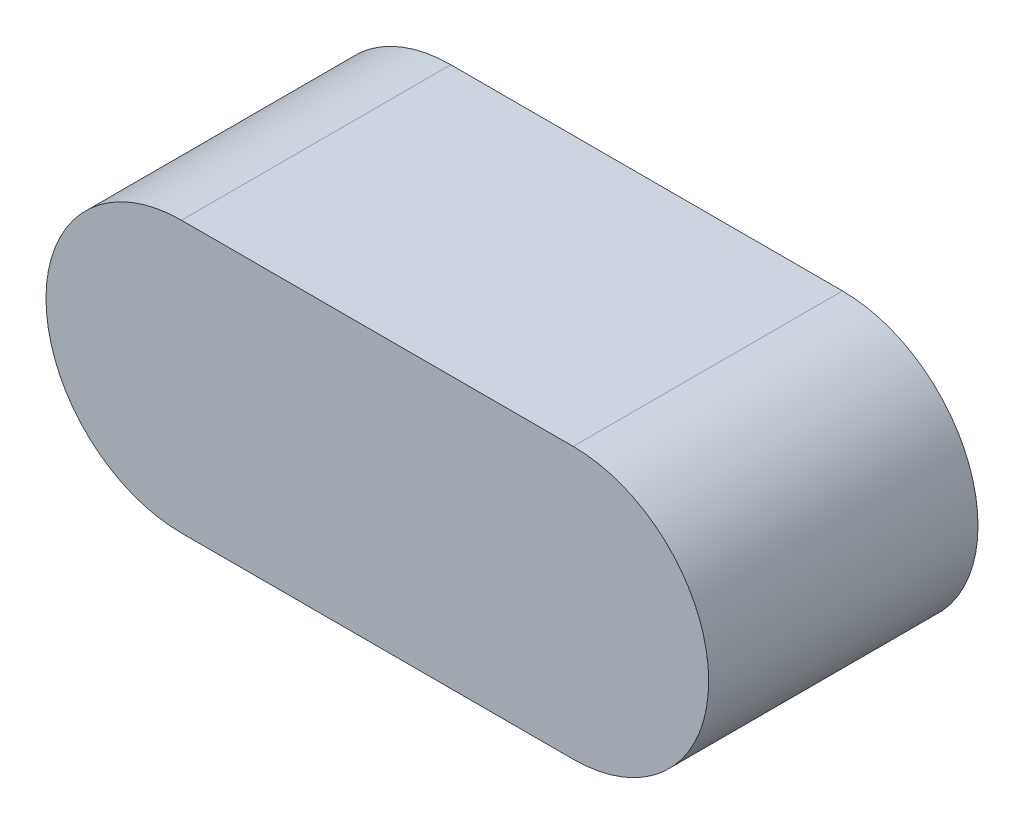
SolidWorks part; units mm, degrees
ref_plane "Plan de face" through (0, 0, 0) normal (0, 0, 1) x (1, 0, 0)
ref_plane "Plan de dessus" through (0, 0, 0) normal (0, 1, 0) x (1, 0, 0)
ref_plane "Plan de droite" through (0, 0, 0) normal (1, 0, 0) x (0, 0, -1)
sketch "Esquisse1" plane through (0, 0, 0) normal (0, 0, 1) x (1, 0, 0)
  line L0 (-120, 0) -> (120, 0) construction
  line L7 (-120, 80) -> (120, 80)
  line L10 (-120, -80) -> (120, -80)
  arc A4 (-120, 80) -> (-120, -80) centre (-120, 0) ccw
  arc A5 (120, -80) -> (120, 80) centre (120, 0) ccw
  point P2 (0, 0)
  point P8 (0, 0)
  point P9 (200, 0)
  point P10 (-200, 0)
  dimension "D1" = 400
  dimension "D2" = 160
extrude "Boss.-Extru.2" add sketch "Esquisse1" along normal blind 162
shell "Coque1" thickness 3
